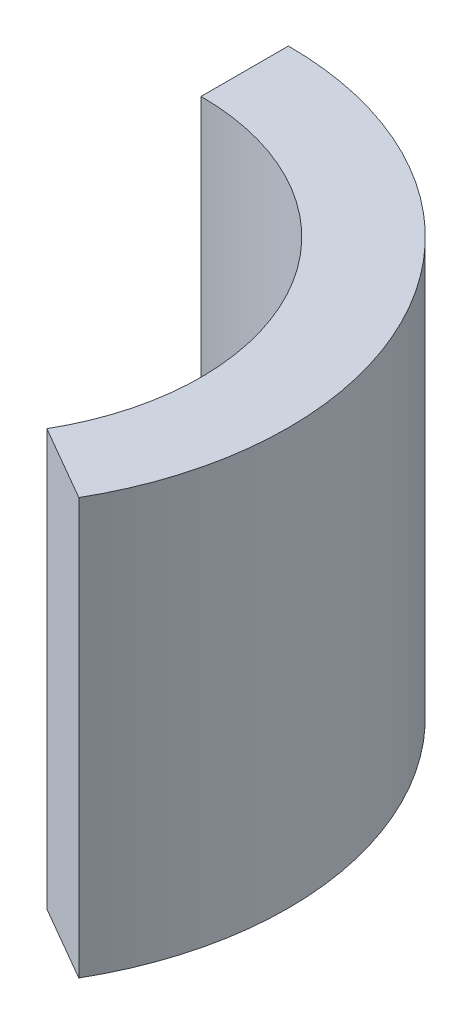
SolidWorks part; units mm, degrees
ref_plane "Front Plane" through (0, 0, 0) normal (0, 0, 1) x (1, 0, 0)
ref_plane "Top Plane" through (0, 0, 0) normal (0, 1, 0) x (1, 0, 0)
ref_plane "Right Plane" through (0, 0, 0) normal (1, 0, 0) x (0, 0, -1)
sketch "Sketch1" plane through (0, 0, 0) normal (0, 1, 0) x (1, 0, 0)
  line L0 (0, 15.135) -> (0, 0)
  line L1 (0, 0) -> (13.1073, -7.5675)
  circle A0 centre (0, 0) radius 15.135
  circle A1 centre (0, 0) radius 11.135
  dimension "D1" = 4
  dimension "D2" = 30.27
  dimension "D3" = 120
extrude "Boss-Extrude1" add sketch "Sketch1" along normal blind 19.05 contours A1 L1 A0 L0
